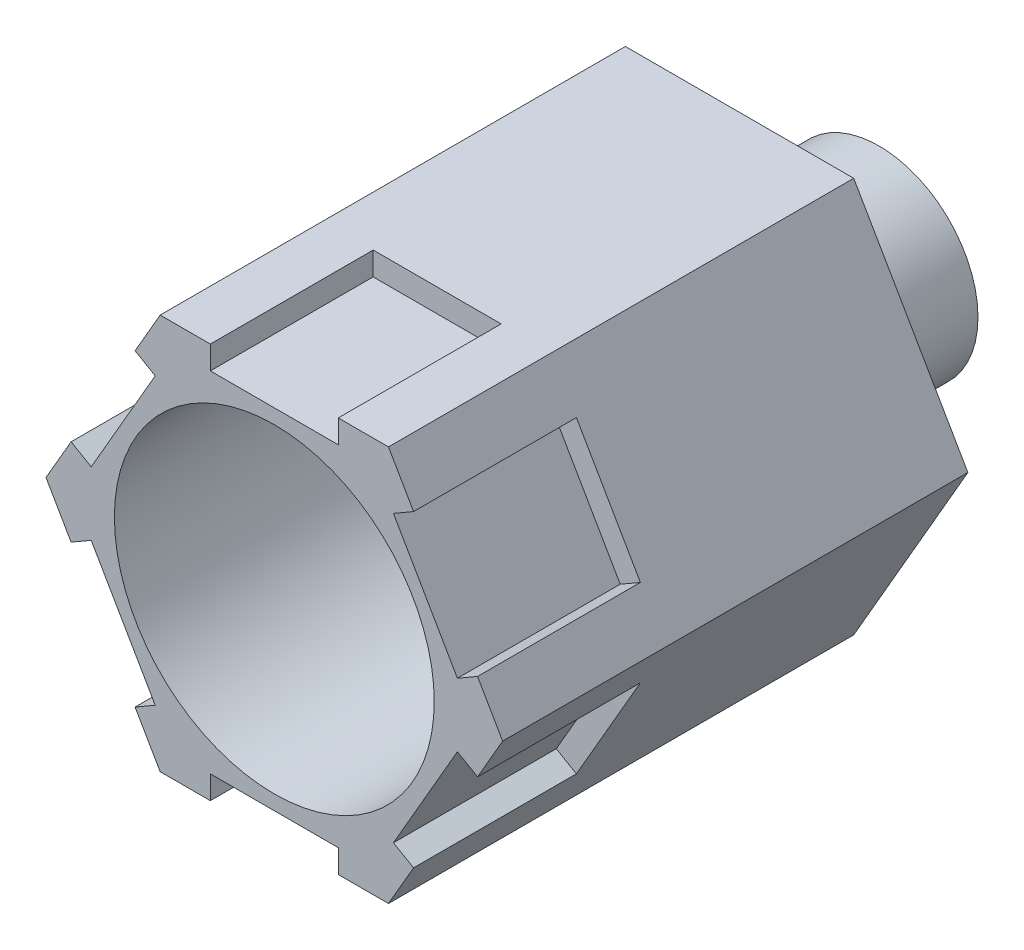
SolidWorks part; units mm, degrees
ref_plane "Plan de face" through (0, 0, 0) normal (0, 0, 1) x (1, 0, 0)
ref_plane "Plan de dessus" through (0, 0, 0) normal (0, 1, 0) x (1, 0, 0)
ref_plane "Plan de droite" through (0, 0, 0) normal (1, 0, 0) x (0, 0, -1)
sketch "Esquisse1" plane through (0, 0, 0) normal (0, 0, 1) x (1, 0, 0)
  line L0 (19.6299, 0) -> (19.6299, 34) construction
  line L2 (39.2598, 17) -> (29.4449, 34)
  line L3 (29.4449, 34) -> (9.815, 34)
  line L4 (9.815, 34) -> (0, 17)
  line L5 (0, 17) -> (9.815, 0)
  line L6 (9.815, 0) -> (29.4449, 0)
  line L7 (29.4449, 0) -> (39.2598, 17)
  circle A0 centre (19.6299, 17) radius 13.75
  circle A1 centre (19.6299, 17) radius 17 construction
  point P0 (17.1767, 0.9893)
  dimension "D3" = 27.5
  dimension "D1" = 34
extrude "Boss.-Extru.1" add sketch "Esquisse1" along normal blind 38
sketch "Esquisse2" plane through (0, 0, 38) normal (0, 0, 1) x (1, 0, 0)
  line L0 (9.815, 0) -> (29.4449, 0) construction
  line L1 (14.1299, 0) -> (25.1299, 0)
  line L2 (14.1299, 0) -> (14.1299, 2)
  line L3 (14.1299, 2) -> (25.1299, 2)
  line L4 (25.1299, 0) -> (25.1299, 2)
  line L5 (19.6299, 2) -> (19.6299, 0) construction
  line L6 (2.1575, 13.2631) -> (7.6575, 3.7369)
  line L7 (2.1575, 13.2631) -> (3.8895, 14.2631)
  line L8 (3.8895, 14.2631) -> (9.3895, 4.7369)
  line L9 (7.6575, 3.7369) -> (9.3895, 4.7369)
  line L10 (6.6395, 9.5) -> (4.9075, 8.5) construction
  line L11 (7.6575, 30.2631) -> (2.1575, 20.7369)
  line L12 (7.6575, 30.2631) -> (9.3895, 29.2631)
  line L13 (9.3895, 29.2631) -> (3.8895, 19.7369)
  line L14 (2.1575, 20.7369) -> (3.8895, 19.7369)
  line L15 (6.6395, 24.5) -> (4.9075, 25.5) construction
  line L16 (25.1299, 34) -> (14.1299, 34)
  line L17 (25.1299, 34) -> (25.1299, 32)
  line L18 (25.1299, 32) -> (14.1299, 32)
  line L19 (14.1299, 34) -> (14.1299, 32)
  line L20 (19.6299, 32) -> (19.6299, 34) construction
  line L21 (37.1023, 20.7369) -> (31.6023, 30.2631)
  line L22 (37.1023, 20.7369) -> (35.3703, 19.7369)
  line L23 (35.3703, 19.7369) -> (29.8703, 29.2631)
  line L24 (31.6023, 30.2631) -> (29.8703, 29.2631)
  line L25 (32.6203, 24.5) -> (34.3523, 25.5) construction
  line L26 (31.6023, 3.7369) -> (37.1023, 13.2631)
  line L27 (31.6023, 3.7369) -> (29.8703, 4.7369)
  line L28 (29.8703, 4.7369) -> (35.3703, 14.2631)
  line L29 (37.1023, 13.2631) -> (35.3703, 14.2631)
  line L30 (32.6203, 9.5) -> (34.3523, 8.5) construction
  point P8 (19.6299, 17)
  point P40 (19.6299, 17)
  dimension "D1" = 2
  dimension "D2" = 11
  dimension "D3" = 6
extrude "Enlèv. mat.-Extru.1" cut sketch "Esquisse2" against normal blind 14
sketch "Esquisse4" plane through (0, 0, 0) normal (0, 0, -1) x (-1, 0, 0)
  line L6 (-39.2598, 17) -> (-29.4449, 0)
  line L7 (-29.4449, 0) -> (-9.815, 0)
  line L8 (-9.815, 0) -> (0, 17)
  line L9 (0, 17) -> (-9.815, 34)
  line L10 (-9.815, 34) -> (-29.4449, 34)
  line L11 (-29.4449, 34) -> (-39.2598, 17)
  line L12 (-39.2598, 17) -> (-29.4449, 0)
  line L13 (-29.4449, 0) -> (-9.815, 0)
  line L14 (-9.815, 0) -> (0, 17)
  line L15 (0, 17) -> (-9.815, 34)
  line L16 (-9.815, 34) -> (-29.4449, 34)
  line L17 (-29.4449, 34) -> (-39.2598, 17)
  dimension "D1" = 0
extrude "Boss.-Extru.2" add sketch "Esquisse4" along normal blind 2
sketch "Esquisse5" plane through (0, 0, -2) normal (0, 0, -1) x (-1, 0, 0)
  line L0 (-19.6299, 0) -> (-19.6299, 34) construction
  line L1 (-29.4449, 0) -> (-9.815, 0) construction
  line L2 (-9.815, 34) -> (-29.4449, 34) construction
  circle A0 centre (-19.6299, 17) radius 8.5
  dimension "D1" = 17
extrude "Boss.-Extru.3" add sketch "Esquisse5" along normal blind 12
sketch "Esquisse6" plane through (0, 0, -2) normal (0, 0, -1) x (-1, 0, 0)
  circle A0 centre (-19.6299, 17) radius 9.5
  point P3 (0, 0)
  point P4 (-19.6299, 17)
  dimension "D1" = 19
extrude "Boss.-Extru.4" add sketch "Esquisse6" along normal blind 1
